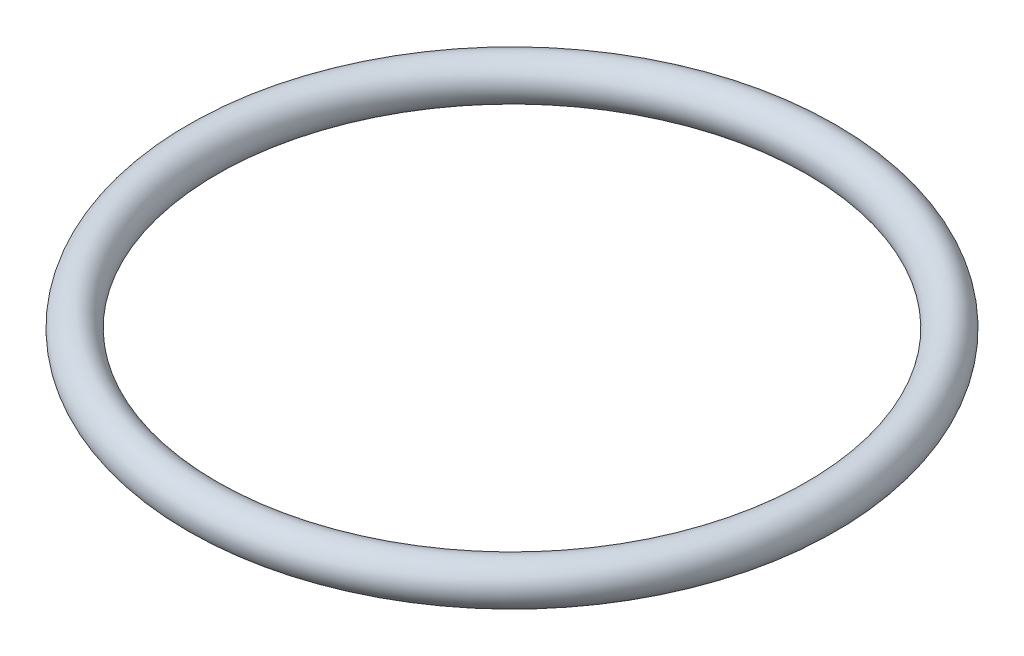
SolidWorks part; units mm, degrees
material "尼龙 6/10"
ref_plane "前视基准面" through (0, 0, 0) normal (0, 0, 1) x (1, 0, 0)
ref_plane "上视基准面" through (0, 0, 0) normal (0, 1, 0) x (1, 0, 0)
ref_plane "右视基准面" through (0, 0, 0) normal (1, 0, 0) x (0, 0, -1)
sketch "草图1" plane through (0, 0, 0) normal (0, 0, 1) x (1, 0, 0)
  line L0 (-7, 0) -> (107, 0) construction
  line L1 (107, 0) -> (107, 22.6508) construction
  circle A0 centre (0, 0) radius 7
  dimension "D1" = 14
  dimension "D2" = 114
revolve "旋转1" add sketch "草图1" angle 360 about L1
